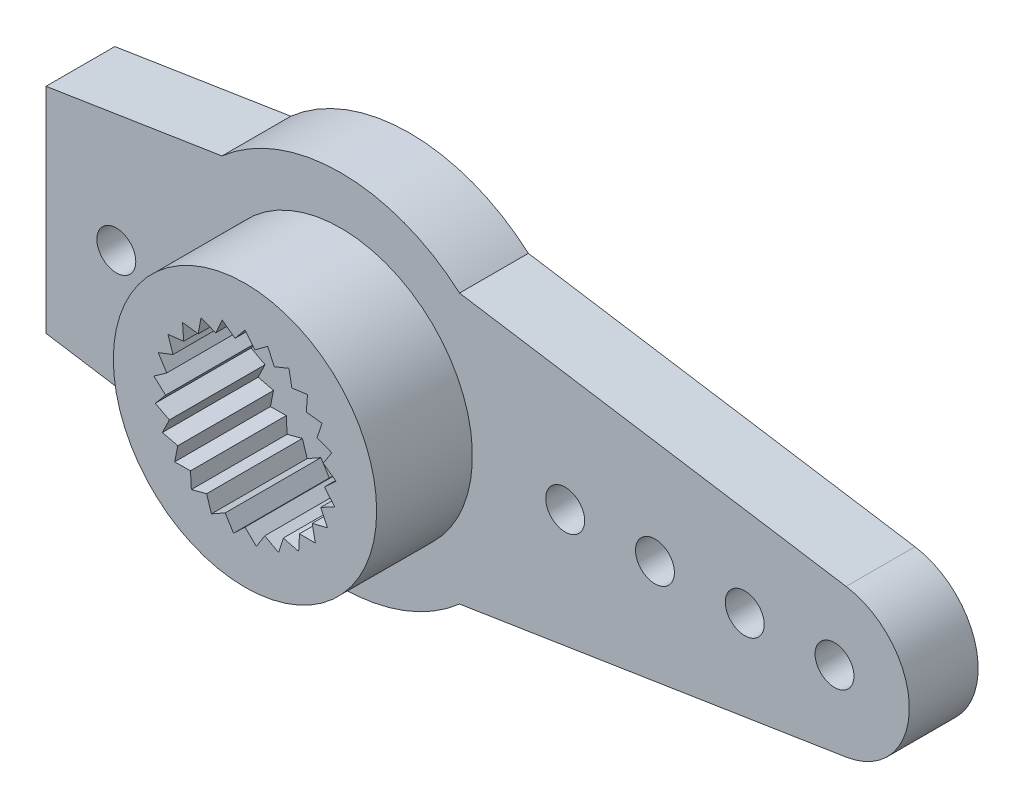
SolidWorks part; units mm, degrees
ref_plane "Front" through (0, 0, 0) normal (0, 0, 1) x (1, 0, 0)
ref_plane "Top" through (0, 0, 0) normal (0, 1, 0) x (1, 0, 0)
ref_plane "Right" through (0, 0, 0) normal (1, 0, 0) x (0, 0, -1)
sketch "Эскиз1" plane through (0, 0, 0) normal (0, 0, 1) x (1, 0, 0)
  line L0 (-3.9686, 4.5) -> (-16.8881, 2.4697)
  line L1 (-19, 4.5) -> (19, 4.5) construction
  line L2 (-19, 4.5) -> (-19, -4.5) construction
  line L3 (-19, -4.5) -> (19, -4.5) construction
  line L4 (19, 4.5) -> (19, -4.5) construction
  line L5 (0, -4.5) -> (0, 4.5) construction
  line L6 (-19, 0) -> (19, 0) construction
  line L7 (-3.9686, -4.5) -> (-16.8881, -2.4697)
  line L8 (3.9686, -4.5) -> (16.8881, -2.4697)
  line L9 (3.9686, 4.5) -> (16.8881, 2.4697)
  circle A0 centre (0, 0) radius 6 construction
  circle A1 centre (-16.5, 0) radius 2.5 construction
  arc A2 (-16.8881, 2.4697) -> (-16.8881, -2.4697) centre (-16.5, 0) ccw
  arc A3 (-3.9686, 4.5) -> (3.9686, 4.5) centre (0, 0) cw
  arc A4 (-3.9686, -4.5) -> (3.9686, -4.5) centre (0, 0) ccw
  circle A5 centre (16.5, 0) radius 2.5 construction
  arc A6 (16.8881, 2.4697) -> (16.8881, -2.4697) centre (16.5, 0) cw
  circle A7 centre (-16.5, 0) radius 0.65
  circle A8 centre (-13.5, 0) radius 0.65
  circle A9 centre (-10.5, 0) radius 0.65
  circle A10 centre (-7.5, 0) radius 0.65
  circle A11 centre (16.5, 0) radius 0.65
  circle A12 centre (7.5, 0) radius 0.65
  circle A13 centre (10.5, 0) radius 0.65
  circle A14 centre (13.5, 0) radius 0.65
  circle A15 centre (0, 0) radius 1.5
  dimension "D1" = 12
  dimension "D4" = 5
  dimension "D5" = 1.3
  dimension "D7" = 3
  dimension "D2" = 9
  dimension "D3" = 38
  dimension "D6" = 4
extrude "Бобышка-Вытянуть1" add sketch "Эскиз1" along normal blind 2.3
sketch "Эскиз2" plane through (0, 0, 2.3) normal (0, 0, 1) x (1, 0, 0)
  line L0 (0, 0) -> (0, 3.05) construction
  line L1 (0, 0) -> (0.3823, 3.0259) construction
  line L2 (0.3334, 2.6394) -> (0, 3.05)
  line L3 (-0.3334, 2.6394) -> (0, 3.05)
  line L4 (0.3334, 2.6394) -> (0.7585, 2.9542)
  line L5 (0.9794, 2.4736) -> (0.7585, 2.9542)
  line L6 (0.9794, 2.4736) -> (1.4693, 2.6727)
  line L7 (1.5638, 2.1523) -> (1.4693, 2.6727)
  line L8 (1.5638, 2.1523) -> (2.0879, 2.2234)
  line L9 (2.0499, 1.6958) -> (2.0879, 2.2234)
  line L10 (2.0499, 1.6958) -> (2.5752, 1.6343)
  line L11 (2.4072, 1.1328) -> (2.5752, 1.6343)
  line L12 (2.4072, 1.1328) -> (2.9007, 0.9425)
  line L13 (2.6133, 0.4985) -> (2.9007, 0.9425)
  line L14 (2.6133, 0.4985) -> (3.044, 0.1915)
  line L15 (2.6552, -0.167) -> (3.044, 0.1915)
  line L16 (2.6552, -0.167) -> (2.996, -0.5715)
  line L17 (2.5302, -0.8221) -> (2.996, -0.5715)
  line L18 (2.5302, -0.8221) -> (2.7597, -1.2986)
  line L19 (2.2463, -1.4255) -> (2.7597, -1.2986)
  line L20 (2.2463, -1.4255) -> (2.3501, -1.9441)
  line L21 (1.8212, -1.9394) -> (2.3501, -1.9441)
  line L22 (1.8212, -1.9394) -> (1.7927, -2.4675)
  line L23 (1.2817, -2.3313) -> (1.7927, -2.4675)
  line L24 (1.2817, -2.3313) -> (1.1228, -2.8358)
  line L25 (0.6616, -2.5768) -> (1.1228, -2.8358)
  line L26 (0.6616, -2.5768) -> (0.3823, -3.0259)
  line L27 (0, -2.6604) -> (0.3823, -3.0259)
  line L28 (0, -2.6604) -> (-0.3823, -3.0259)
  line L29 (-0.6616, -2.5768) -> (-0.3823, -3.0259)
  line L30 (-0.6616, -2.5768) -> (-1.1228, -2.8358)
  line L31 (-1.2817, -2.3313) -> (-1.1228, -2.8358)
  line L32 (-1.2817, -2.3313) -> (-1.7927, -2.4675)
  line L33 (-1.8212, -1.9394) -> (-1.7927, -2.4675)
  line L34 (-1.8212, -1.9394) -> (-2.3501, -1.9441)
  line L35 (-2.2463, -1.4255) -> (-2.3501, -1.9441)
  line L36 (-2.2463, -1.4255) -> (-2.7597, -1.2986)
  line L37 (-2.5302, -0.8221) -> (-2.7597, -1.2986)
  line L38 (-2.5302, -0.8221) -> (-2.996, -0.5715)
  line L39 (-2.6552, -0.167) -> (-2.996, -0.5715)
  line L40 (-2.6552, -0.167) -> (-3.044, 0.1915)
  line L41 (-2.6133, 0.4985) -> (-3.044, 0.1915)
  line L42 (-2.6133, 0.4985) -> (-2.9007, 0.9425)
  line L43 (-2.4072, 1.1328) -> (-2.9007, 0.9425)
  line L44 (-2.4072, 1.1328) -> (-2.5752, 1.6343)
  line L45 (-2.0499, 1.6958) -> (-2.5752, 1.6343)
  line L46 (-2.0499, 1.6958) -> (-2.0879, 2.2234)
  line L47 (-1.5638, 2.1523) -> (-2.0879, 2.2234)
  line L48 (-1.5638, 2.1523) -> (-1.4693, 2.6727)
  line L49 (-0.9794, 2.4736) -> (-1.4693, 2.6727)
  line L50 (-0.9794, 2.4736) -> (-0.7585, 2.9542)
  line L51 (-0.3334, 2.6394) -> (-0.7585, 2.9542)
  circle A0 centre (0, 0) radius 4.4
  circle A1 centre (0, 0) radius 3.05 construction
  circle A2 centre (0, 0) radius 2.65 construction
  point P83 (0, 0)
  dimension "D1" = 8.8
  dimension "D2" = 6.1
  dimension "D3" = 5.3
  dimension "D5" = 25
  dimension "D4" = 7.2
extrude "Бобышка-Вытянуть2" add sketch "Эскиз2" along normal blind 3.2
sketch "Эскиз3" plane through (0, 0, 0) normal (0, 0, -1) x (-1, 0, 0)
  circle A0 centre (0, 0) radius 4.4
  circle A1 centre (0, 0) radius 3.4
  circle A2 centre (0, 0) radius 2.75
  circle M17 centre (0, 0) radius 1.5
  dimension "D1" = 8.8
  dimension "D2" = 6.8
  dimension "D3" = 5.5
extrude "Вырез-Вытянуть1" cut sketch "Эскиз3" against normal blind 1 contours A0 A1 | A2 M17
sketch "Sketch1" plane through (0, 0, 0) normal (0, 0, -1) x (-1, 0, 0)
  line L2 (9.85, 7.501) -> (22.1956, 7.501)
  line L3 (9.85, 7.501) -> (9.85, -8.9766)
  line L12 (9.85, -8.9766) -> (22.1956, -8.9766)
  line L13 (22.1956, 7.501) -> (22.1956, -8.9766)
extrude "Cut-Extrude2" cut sketch "Sketch1" against normal blind 10
